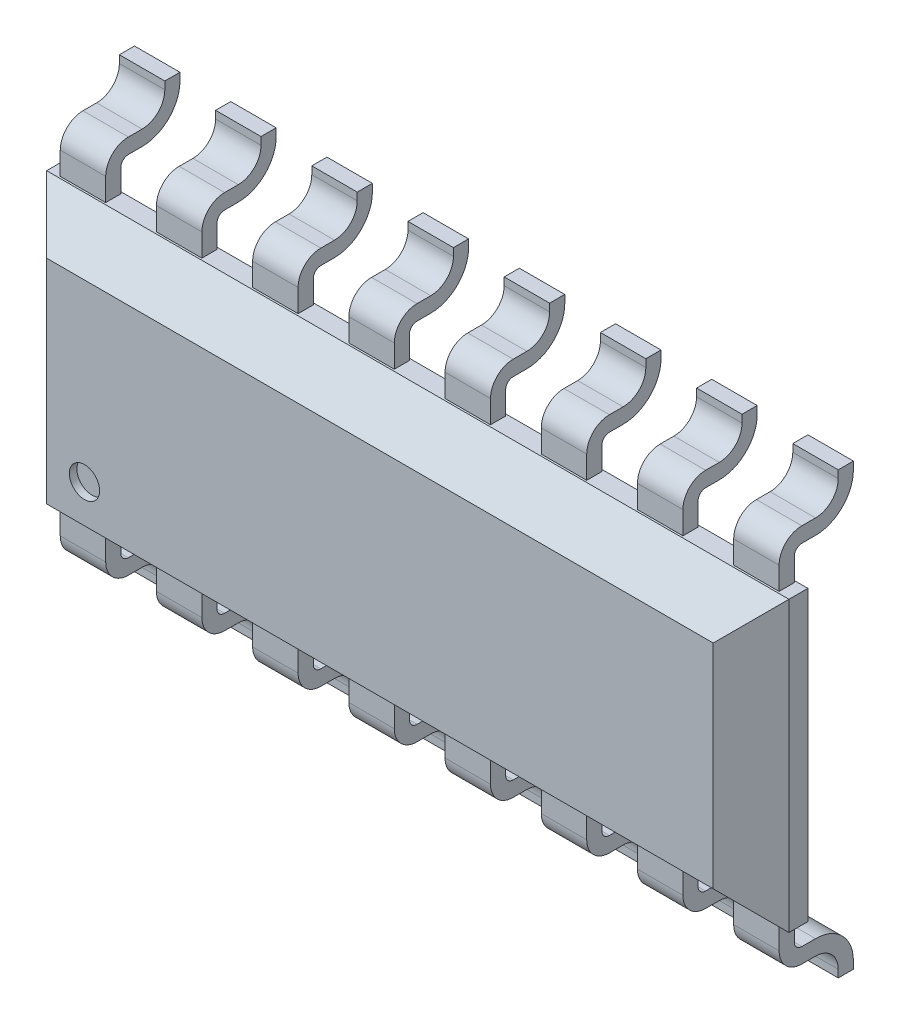
SolidWorks part; units mm, degrees
ref_plane "前视基准面" through (0, 0, 0) normal (0, 0, 1) x (1, 0, 0)
ref_plane "上视基准面" through (0, 0, 0) normal (0, 1, 0) x (1, 0, 0)
ref_plane "右视基准面" through (0, 0, 0) normal (1, 0, 0) x (0, 0, -1)
sketch "草图1" plane through (0, 0, 0) normal (0, 0, 1) x (1, 0, 0)
  line L0 (-1000, 0) -> (49000, 0) construction
  line L1 (0, -1000) -> (0, 49000) construction
  line L2 (-4.9, 1.905) -> (4.9, 1.905)
  line L3 (4.9, 1.905) -> (4.9, -1.905)
  line L4 (-4.9, -1.905) -> (4.9, -1.905)
  line L5 (-4.9, 1.905) -> (-4.9, -1.905)
  point P9 (4.9, 0)
  point P11 (0, -1.905)
  point P12 (0, 1.905)
  dimension "D1" = 9.8
  dimension "D2" = 3.81
extrude "凸台-拉伸1" add sketch "草图1" along normal blind 1.25
chamfer "倒角1" distance 0.5 angle 45 8 edges at (4.9, 0, 0) (0, 1.905, 0) (-4.9, 0, 0) (0, -1.905, 0) (4.9, 0, 1.25) (0, 1.905, 1.25) (0, -1.905, 1.25) (-4.9, 0, 1.25)
sketch "草图2" plane through (0, -1.905, 0) normal (0, -1, 0) x (1, 0, 0)
  line L0 (0, 0.75) -> (0, 0.5) construction
  line L1 (4.9, 0.75) -> (-4.9, 0.75) construction
  line L2 (-4.9, 0.5) -> (4.9, 0.5) construction
  line L3 (4.9, 0.625) -> (-4.9, 0.625) construction
  line L4 (4.9, 0.75) -> (4.9, 0.5) construction
  line L5 (-4.9, 0.75) -> (-4.9, 0.5) construction
  line L6 (-0.635, 0.75) -> (-0.635, 0.5) construction
  line L7 (-0.335, 0.725) -> (-0.935, 0.725)
  line L8 (-0.935, 0.725) -> (-0.935, 0.525)
  line L9 (-0.335, 0.525) -> (-0.935, 0.525)
  line L10 (-0.335, 0.725) -> (-0.335, 0.525)
  point P18 (-0.935, 0.625)
  point P20 (-0.635, 0.525)
  point P21 (-0.635, 0.725)
  dimension "D1" = 0.635
  dimension "D2" = 0.2
  dimension "D3" = 0.6
ref_plane "基准面1" through (-0.635, 0, 0) normal (1, 0, 0) x (0, 0, -1)
sketch "草图3" plane through (-0.635, 0, 0) normal (1, 0, 0) x (0, 0, -1)
  line L2 (-0.725, -1.905) -> (-0.725, -2.205)
  line L3 (0.0555, -2.905) -> (0.0555, -2.805)
  line L4 (-0.425, -2.505) -> (-0.2445, -2.505)
  arc A0 (0.0555, -2.805) -> (-0.2445, -2.505) centre (-0.2445, -2.805) ccw
  arc A1 (-0.425, -2.505) -> (-0.725, -2.205) centre (-0.425, -2.205) cw
  point P5 (0.0555, -2.505)
  dimension "D3" = 0.3
  dimension "D1" = 0.4
  dimension "D2" = 1
sweep "扫描1" add profiles "草图2" path "草图3"
pattern_linear "阵列(线性)1" count 4 spacing 1.27 along (-1, 0, 0) of "扫描1"
pattern_linear "阵列(线性)2" count 5 spacing 1.27 along (1, 0, 0) of "扫描1"
mirror "镜向1" about plane through (0, 0, 0) normal (0, 1, 0) of "扫描1", "阵列(线性)1", "阵列(线性)2"
sketch "草图4" plane through (0, 0, 1.25) normal (0, 0, 1) x (1, 0, 0)
  line L0 (-4.9, -1.905) -> (-4.9, 1.905) construction
  line L1 (4.9, -1.905) -> (-4.9, -1.905) construction
  circle A0 centre (-3.9, -0.905) radius 0.2
  dimension "D1" = 0.4
  dimension "D2" = 1
  dimension "D3" = 1
extrude "切除-拉伸1" cut sketch "草图4" against normal blind 0.1
